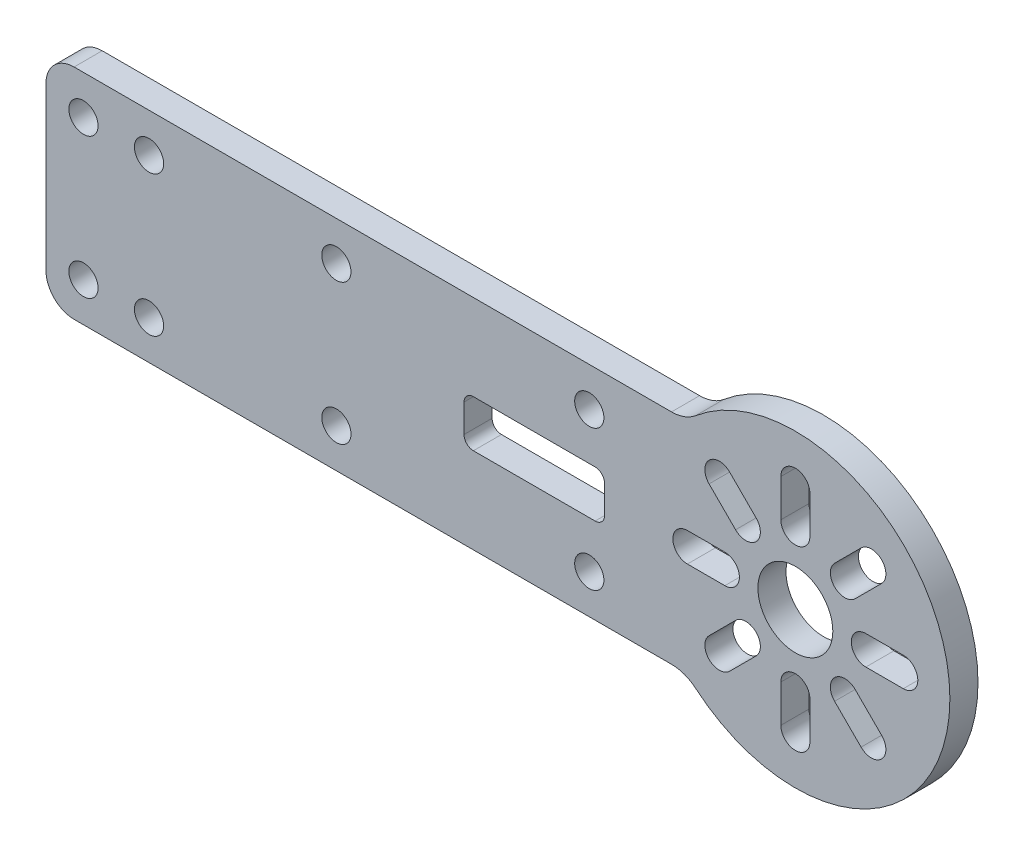
SolidWorks part; units mm, degrees
ref_plane "前视基准面" through (0, 0, 0) normal (0, 0, 1) x (1, 0, 0)
ref_plane "上视基准面" through (0, 0, 0) normal (0, 1, 0) x (1, 0, 0)
ref_plane "右视基准面" through (0, 0, 0) normal (1, 0, 0) x (0, 0, -1)
other "Configuration Table"
sketch "草图1" plane through (0, 0, 0) normal (0, 0, 1) x (1, 0, 0)
  line L10 (0, 0) -> (-11.6673, 11.6673) construction
  line L13 (-7.5258, 0) -> (-11.5258, 0) construction
  line L14 (-11.5258, 0) -> (-7.5258, 0) construction
  line L15 (-11.5258, 1.55) -> (-7.5258, 1.55)
  line L16 (-11.5258, -1.55) -> (-7.5258, -1.55)
  line L19 (11.5258, 0) -> (7.5258, 0) construction
  line L21 (11.5258, 1.55) -> (7.5258, 1.55)
  line L22 (11.5258, -1.55) -> (7.5258, -1.55)
  line L25 (-8.1135, 8.1135) -> (-5.2851, 5.2851) construction
  line L26 (-7.0175, 9.2095) -> (-4.1891, 6.3811)
  line L27 (-9.2095, 7.0175) -> (-6.3811, 4.1891)
  line L28 (0, -11.4742) -> (0, -7.4742) construction
  line L29 (1.55, -11.4742) -> (1.55, -7.4742)
  line L30 (-1.55, -11.4742) -> (-1.55, -7.4742)
  line L31 (0, 0) -> (-11.6673, -11.6673) construction
  line L32 (0, 11.5258) -> (0, 7.5258) construction
  line L33 (1.55, 11.5258) -> (1.55, 7.5258)
  line L34 (-1.55, 11.5258) -> (-1.55, 7.5258)
  line L35 (8.1135, 8.1135) -> (5.2851, 5.2851) construction
  line L36 (7.0175, 9.2095) -> (4.1891, 6.3811)
  line L37 (9.2095, 7.0175) -> (6.3811, 4.1891)
  line L38 (-8.1135, -8.1135) -> (-5.2851, -5.2851) construction
  line L39 (-7.0175, -9.2095) -> (-4.1891, -6.3811)
  line L40 (-9.2095, -7.0175) -> (-6.3811, -4.1891)
  line L41 (8.1135, -8.1135) -> (5.2851, -5.2851) construction
  line L42 (7.0175, -9.2095) -> (4.1891, -6.3811)
  line L43 (9.2095, -7.0175) -> (6.3811, -4.1891)
  line L44 (0, 0) -> (-76, 0) construction
  line L45 (-13.2207, 11.6673) -> (-77, 11.6673)
  line L46 (-13.2207, -11.6673) -> (-77, -11.6673)
  line L47 (-80, 8.6673) -> (-80, -8.6673)
  line L48 (-76, 7.5) -> (-76, -7.5) construction
  line L50 (-34.3733, 2.5) -> (-21.3733, 2.5)
  line L51 (-35.3733, 1.5) -> (-35.3733, -1.5)
  line L52 (-34.3733, -2.5) -> (-21.3733, -2.5)
  line L53 (-20.3733, 1.5) -> (-20.3733, -1.5)
  line L54 (-35.3733, 2.5) -> (-20.3733, -2.5) construction
  line L55 (-35.3733, -2.5) -> (-20.3733, 2.5) construction
  circle A19 centre (0, 0) radius 4
  arc A21 (-11.5258, 1.55) -> (-11.5258, -1.55) centre (-11.5258, 0) ccw
  arc A22 (-7.5258, -1.55) -> (-7.5258, 1.55) centre (-7.5258, 0) ccw
  arc A23 (11.5258, 1.55) -> (11.5258, -1.55) centre (11.5258, 0) cw
  arc A24 (7.5258, -1.55) -> (7.5258, 1.55) centre (7.5258, 0) cw
  arc A25 (-7.0175, 9.2095) -> (-9.2095, 7.0175) centre (-8.1135, 8.1135) ccw
  arc A26 (-6.3811, 4.1891) -> (-4.1891, 6.3811) centre (-5.2851, 5.2851) ccw
  arc A27 (1.55, -11.4742) -> (-1.55, -11.4742) centre (0, -11.4742) cw
  arc A28 (-1.55, -7.4742) -> (1.55, -7.4742) centre (0, -7.4742) cw
  arc A29 (1.55, 11.5258) -> (-1.55, 11.5258) centre (0, 11.5258) ccw
  arc A30 (-1.55, 7.5258) -> (1.55, 7.5258) centre (0, 7.5258) ccw
  arc A31 (7.0175, 9.2095) -> (9.2095, 7.0175) centre (8.1135, 8.1135) cw
  arc A32 (6.3811, 4.1891) -> (4.1891, 6.3811) centre (5.2851, 5.2851) cw
  arc A33 (-7.0175, -9.2095) -> (-9.2095, -7.0175) centre (-8.1135, -8.1135) cw
  arc A34 (-6.3811, -4.1891) -> (-4.1891, -6.3811) centre (-5.2851, -5.2851) cw
  arc A35 (7.0175, -9.2095) -> (9.2095, -7.0175) centre (8.1135, -8.1135) ccw
  arc A36 (6.3811, -4.1891) -> (4.1891, -6.3811) centre (5.2851, -5.2851) ccw
  arc A37 (-10.6411, 12.6102) -> (-10.6411, -12.6102) centre (0, 0) cw
  circle A38 centre (-76, 7.5) radius 1.56
  circle A39 centre (-76, -7.5) radius 1.56
  arc A44 (-77, 11.6673) -> (-80, 8.6673) centre (-77, 8.6673) ccw
  arc A45 (-77, -11.6673) -> (-80, -8.6673) centre (-77, -8.6673) cw
  arc A46 (-10.6411, -12.6102) -> (-13.2207, -11.6673) centre (-13.2207, -15.6673) ccw
  arc A47 (-10.6411, 12.6102) -> (-13.2207, 11.6673) centre (-13.2207, 15.6673) cw
  circle A50 centre (-69, 7.5) radius 1.56
  circle A51 centre (-69, -7.5) radius 1.56
  circle A52 centre (-49, 7.5) radius 1.56
  circle A53 centre (-49, -7.5) radius 1.56
  circle A54 centre (-22, 7.5) radius 1.56
  circle A55 centre (-22, -7.5) radius 1.56
  arc A56 (-34.3733, 2.5) -> (-35.3733, 1.5) centre (-34.3733, 1.5) ccw
  arc A57 (-35.3733, -1.5) -> (-34.3733, -2.5) centre (-34.3733, -1.5) ccw
  arc A58 (-21.3733, -2.5) -> (-20.3733, -1.5) centre (-21.3733, -1.5) ccw
  arc A59 (-21.3733, 2.5) -> (-20.3733, 1.5) centre (-21.3733, 1.5) cw
  point P2 (-9.5258, 0)
  point P13 (9.5258, 0)
  point P21 (0, 0)
  point P23 (-6.6993, 6.6993)
  point P30 (0, -9.4742)
  point P36 (0, 9.5258)
  point P43 (6.6993, 6.6993)
  point P50 (-6.6993, -6.6993)
  point P57 (6.6993, -6.6993)
  point P65 (-9.5258, 0)
  point P69 (-76, 0)
  point P74 (-27.8733, 0)
  point P82 (-80, 11.6673)
  point P85 (-80, -11.6673)
  point P88 (-11.6673, -11.6673)
  dimension "D1" = 15
  dimension "D6" = 3
  dimension "D7" = 3
  dimension "D8" = 4
  dimension "D9" = 4
  dimension "D5" = 2
  dimension "D12" = 1
  dimension "D2" = 76
  dimension "D3" = 16.5
  dimension "D4" = 23.3345
  dimension "D10" = 80
  dimension "D11" = 3
extrude "凸台-拉伸3" add sketch "草图1" along normal blind 3
